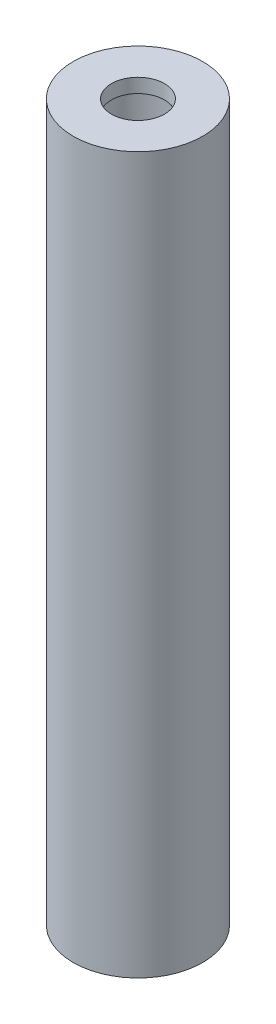
SolidWorks part; units mm, degrees
ref_plane "Front Plane" through (0, 0, 0) normal (0, 0, 1) x (1, 0, 0)
ref_plane "Top Plane" through (0, 0, 0) normal (0, 1, 0) x (1, 0, 0)
ref_plane "Right Plane" through (0, 0, 0) normal (1, 0, 0) x (0, 0, -1)
sketch "Sketch1" plane through (0, 0, 0) normal (0, 1, 0) x (1, 0, 0)
  circle A0 centre (0, 0) radius 2.9083
  circle A1 centre (0, 0) radius 1.524
  dimension "D1" = 5.8166
  dimension "D2" = 3.048
extrude "Boss-Extrude1" add sketch "Sketch1" along normal blind 32.131
sketch "Sketch2" plane through (0, 0, 0) normal (0, 0, 1) x (1, 0, 0)
  line L0 (4.0423, 28.956) -> (-4.0423, 28.956) construction
  line L1 (2.9083, 32.131) -> (-2.9083, 32.131) construction
  point P3 (0, 28.956)
  dimension "D1" = 3.175
ref_plane "Plane1" through (0, 28.956, 0) normal (0, 1, 0) x (1, 0, 0)
sketch "Sketch3" plane through (0, 28.956, 0) normal (0, 1, 0) x (1, 0, 0)
  circle A0 centre (0, 0) radius 1.397
  dimension "D1" = 2.794
extrude "Boss-Extrude2" [suppressed] add sketch "Sketch3" along normal blind 8.6614
sketch "Sketch4" [suppressed] plane through (0, 10.795, 0) normal (0, 1, 0) x (1, 0, 0)
  circle A0 centre (0, 0) radius 1.397
  circle A1 centre (0, 0) radius 1.524
  circle A5 centre (0, 0) radius 1.397 construction
  circle A6 centre (0, 0) radius 1.524 construction
extrude "Boss-Extrude3" [suppressed] add sketch "Sketch4" along normal up to surface (3.175 mm away)
ref_plane "Plane2" [suppressed] through (0, 0.635, 0) normal (0, -1, 0) x (-1, 0, 0)
sketch "Sketch5" [suppressed] plane through (0, 0, 0) normal (0, -1, 0) x (1, 0, 0)
  circle A0 centre (0, 0) radius 1.1906
  circle A1 centre (0, 0) radius 1.524
  circle A2 centre (0, 0) radius 1.524 construction
  dimension "D1" = 2.3813
extrude "Boss-Extrude4" [suppressed] add sketch "Sketch5" against normal up to surface (0.635 mm away)
sketch "Sketch6" [suppressed] plane through (0, 0.635, 0) normal (0, -1, 0) x (-1, 0, 0)
  circle A0 centre (0, 0) radius 1.778
  dimension "D1" = 3.556
extrude "Cut-Extrude1" [suppressed] cut sketch "Sketch6" against normal blind 3.175
ref_plane "Plane3" through (0, 31.496, 0) normal (0, 1, 0) x (1, 0, 0)
sketch "Sketch7" plane through (0, 32.131, 0) normal (0, 1, 0) x (1, 0, 0)
  circle A0 centre (0, 0) radius 1.1906
  circle A1 centre (0, 0) radius 1.524
  circle A2 centre (0, 0) radius 1.524 construction
  dimension "D1" = 2.3813
extrude "Boss-Extrude5" add sketch "Sketch7" against normal up to surface (0.635 mm away) up to plane "Plane3"
sketch "Sketch8" plane through (0, 31.496, 0) normal (0, 1, 0) x (1, 0, 0)
  circle A0 centre (0, 0) radius 1.7859
  dimension "D1" = 3.5719
extrude "Cut-Extrude2" cut sketch "Sketch8" against normal blind 3.175
equation "\"rasPiHoleDiam\"=0.11"
equation "\"rasPiHolHorBet\"=2.035"
equation "\"rasPiHolVerBet\"=2.395"
equation "\"housingStabbyHeights\"=0.395"
equation "\"housingChannelWidth\"= 0.55"
equation "\"housingChannelHeight\"=0.275"
equation "\"housingPiStandOff\"=0.234"
equation "\"housingPiStandOffHeight\"=0.15"
equation "\"D1@Sketch1\"=\"housingPiStandOff\" - .005"
equation "\"D2@Sketch1\"=\"rasPiHoleDiam\"+.01"
equation "\"grovePiStandOff\"=0.675"
equation "\"servoHATfromGPI\"=0.55"
equation "\"servoHATfromRPI\"=1.265"
equation "\"grovePiStandStabbyWithin\"=0.125"
equation "\"D1@Sketch2\"=\"grovePiStandStabbyWithin\""
equation "\"D1@Sketch3\"=\"rasPiHoleDiam\""
equation "\"grovePiStabbyHeight\"=0.341"
equation "\"D1@Boss-Extrude2\"=\"grovePiStabbyHeight\""
equation "\"groveHoleDiam\"=0.09375"
equation "\"railTrackWidth\"=0.135"
equation "\"railWidth\"=0.375\t"
equation "\"railEdgeToCenter\"=1.2825"
equation "\"groveHoleBetween\"=0.78125"
equation "\"grovePegLength\"=0.125"
equation "\"grovePegStickOut\"=0.125"
equation "\"D1@Sketch5\"=\"groveHoleDiam\""
equation "\"D1@Cut-Extrude1\"=\"grovePegLength\""
equation "\"D1@Sketch7\"=\"groveHoleDiam\""
equation "\"D1@Sketch8\"= 3 * \"groveHoleDiam\" / 2"
equation "\"D1@Cut-Extrude2\"=\"grovePegLength\""
